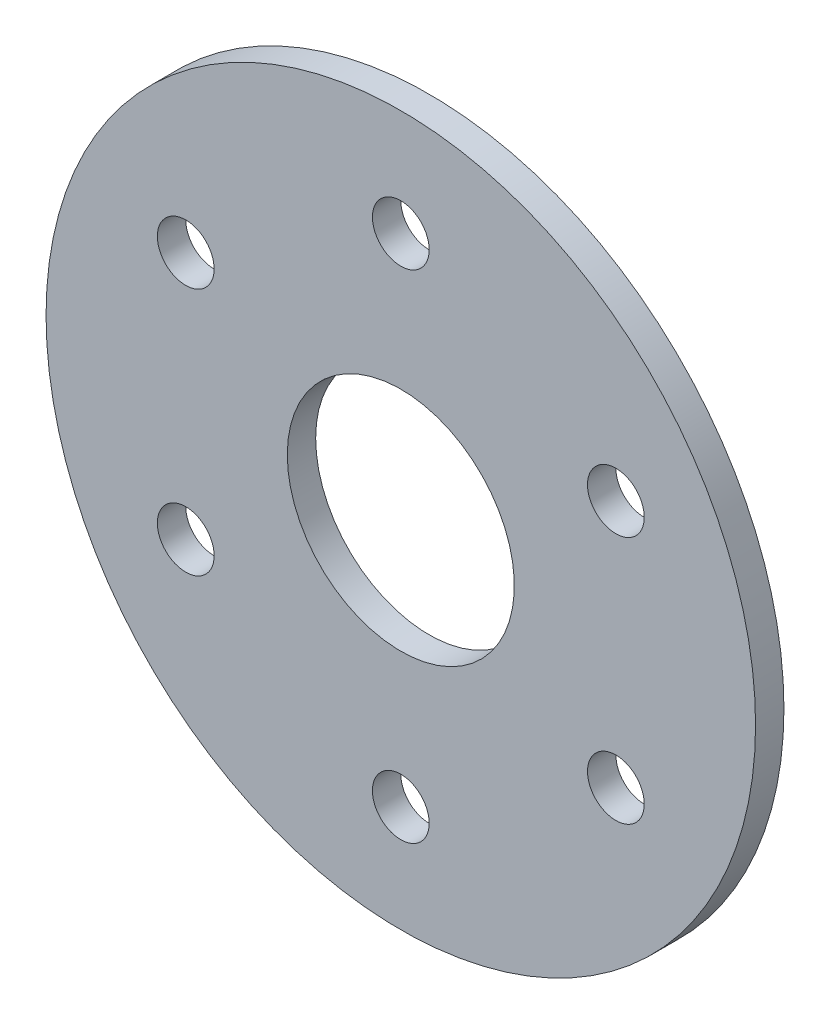
SolidWorks part; units mm, degrees
ref_plane "Front Plane" through (0, 0, 0) normal (0, 0, 1) x (1, 0, 0)
ref_plane "Top Plane" through (0, 0, 0) normal (0, 1, 0) x (1, 0, 0)
ref_plane "Right Plane" through (0, 0, 0) normal (1, 0, 0) x (0, 0, -1)
sketch "Sketch1" plane through (0, 0, 0) normal (0, 0, 1) x (1, 0, 0)
  circle A0 centre (0, 0) radius 12.5
  dimension "D1" = 25
extrude "Boss-Extrude1" add sketch "Sketch1" along normal blind 1
sketch "Sketch2" plane through (0, 0, 0) normal (0, 0, 1) x (1, 0, 0)
  line L0 (0, 5) -> (0, 12.5) construction
  circle A0 centre (0, 0) radius 5 construction
  circle A1 centre (0, 8.75) radius 1
  circle A2 centre (0, 0) radius 12.5 construction
  dimension "D1" = 10
  dimension "D2" = 2
extrude "Cut-Extrude2" cut sketch "Sketch2" against normal blind 2 and the other way through all
sketch "Sketch3" plane through (0, 0, 0) normal (1, 0, 0) x (0, 0, -1)
  line L0 (-8.7222, 0) -> (7.4831, 0) construction
pattern_circular "CirPattern1" count 6 over 360 about axis through (0, 0, 0) along (0, 0, 1) of "Cut-Extrude2"
sketch "Sketch4" plane through (0, 0, 0) normal (0, 0, -1) x (-1, 0, 0)
  circle A0 centre (0, 0) radius 4
  dimension "D1" = 8
extrude "Cut-Extrude3" cut sketch "Sketch4" against normal through all both and the other way through all
